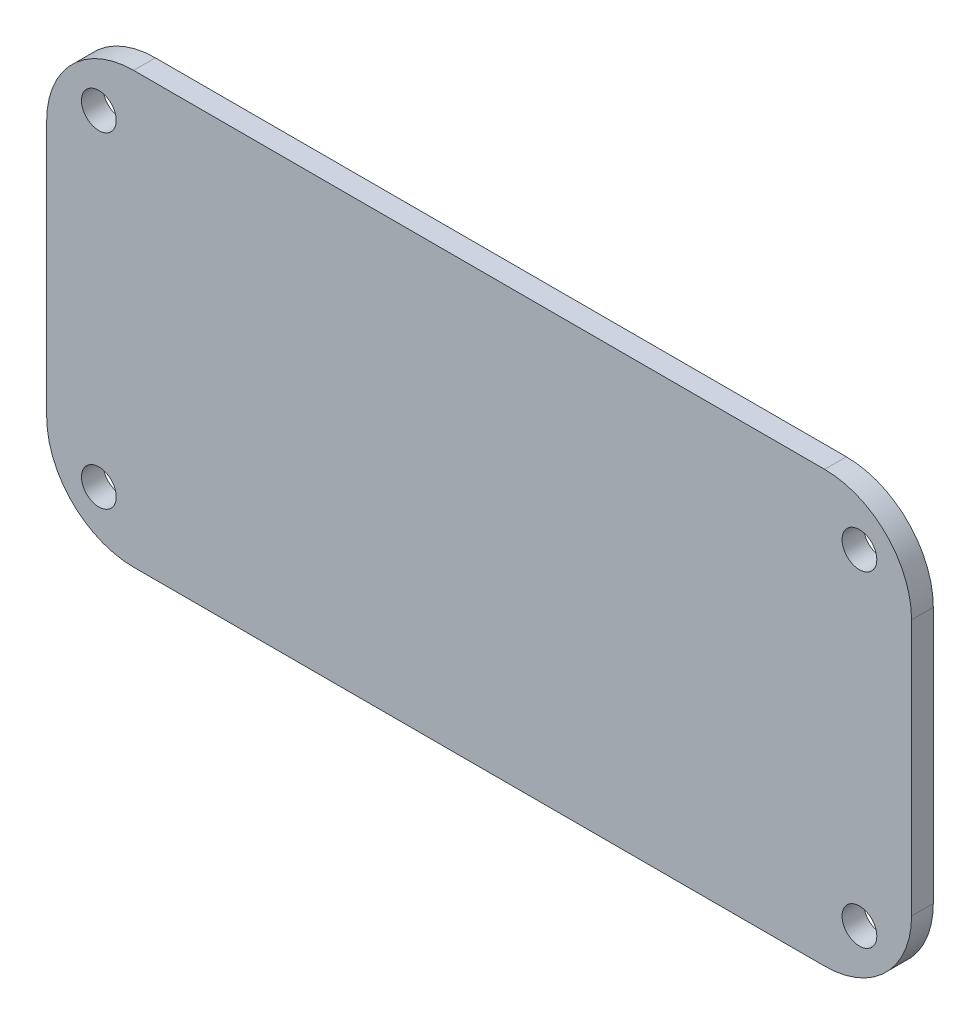
SolidWorks part; units mm, degrees
ref_plane "Front Plane" through (0, 0, 0) normal (0, 0, 1) x (1, 0, 0)
ref_plane "Top Plane" through (0, 0, 0) normal (0, 1, 0) x (1, 0, 0)
ref_plane "Right Plane" through (0, 0, 0) normal (1, 0, 0) x (0, 0, -1)
sketch "Sketch1" plane through (0, 0, 0) normal (0, 0, 1) x (1, 0, 0)
  line L0 (39.8, -11.8) -> (39.8, 11.8)
  line L1 (31.8, 19.8) -> (-31.8, 19.8)
  line L2 (-39.8, 11.8) -> (-39.8, -11.8)
  line L3 (-31.8, -19.8) -> (31.8, -19.8)
  line L4 (0, 19.8) -> (0, 0) construction
  line L5 (39.8, 0) -> (0, 0) construction
  line L7 (-35, -15) -> (35, -15) construction
  line L8 (-35, -15) -> (-35, 15) construction
  line L9 (-35, 15) -> (35, 15) construction
  line L10 (35, -15) -> (35, 15) construction
  line L11 (-35, -15) -> (35, 15) construction
  line L12 (-35, 15) -> (35, -15) construction
  arc A0 (31.8, -19.8) -> (39.8, -11.8) centre (31.8, -11.8) ccw
  arc A1 (39.8, 11.8) -> (31.8, 19.8) centre (31.8, 11.8) ccw
  arc A2 (-31.8, 19.8) -> (-39.8, 11.8) centre (-31.8, 11.8) ccw
  arc A3 (-39.8, -11.8) -> (-31.8, -19.8) centre (-31.8, -11.8) ccw
  circle A4 centre (-35, 15) radius 1.6
  circle A5 centre (35, 15) radius 1.6
  circle A6 centre (35, -15) radius 1.6
  circle A7 centre (-35, -15) radius 1.6
  dimension "D3" = 8
  dimension "D4" = 8
  dimension "D5" = 8
  dimension "D6" = 8
  dimension "D9" = 3.2
  dimension "D10" = 3.2
  dimension "D11" = 3.2
  dimension "D12" = 3.2
  dimension "D1" = 79.6
  dimension "D2" = 39.6
  dimension "D7" = 70
  dimension "D8" = 30
extrude "Boss-Extrude1" add sketch "Sketch1" along normal blind 2
